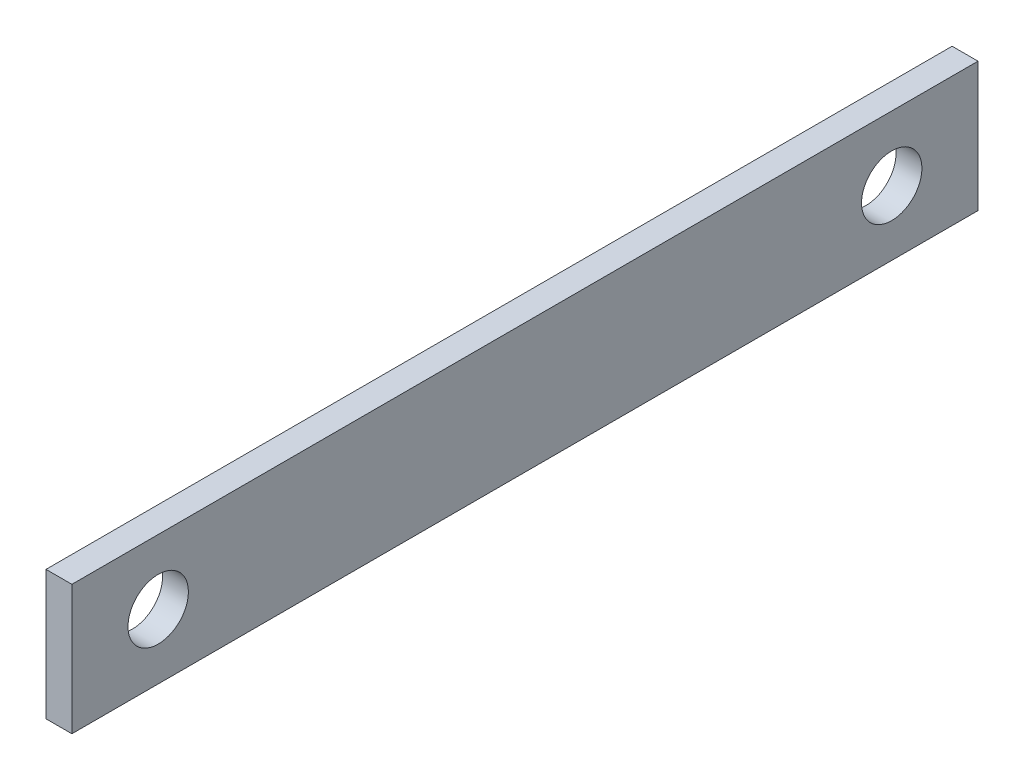
SolidWorks part; units mm, degrees
material "ASTM A36 Steel"
ref_plane "Front Plane" through (0, 0, 0) normal (0, 0, 1) x (1, 0, 0)
ref_plane "Top Plane" through (0, 0, 0) normal (0, 1, 0) x (1, 0, 0)
ref_plane "Right Plane" through (0, 0, 0) normal (1, 0, 0) x (0, 0, -1)
sketch "Sketch1" plane through (0, 0, 0) normal (1, 0, 0) x (0, 0, -1)
  line L1 (-105, -15) -> (105, -15)
  line L2 (-105, -15) -> (-105, 15)
  line L3 (-105, 15) -> (105, 15)
  line L4 (105, -15) -> (105, 15)
  line L5 (-105, -15) -> (105, 15) construction
  line L6 (-105, 15) -> (105, -15) construction
  circle A0 centre (-85, 0) radius 7
  circle A1 centre (85, 0) radius 7
  point P0 (0, 0)
  dimension "D3" = 14
  dimension "D4" = 14
  dimension "D5" = 20
  dimension "D6" = 20
  dimension "D1" = 30
  dimension "D2" = 210
extrude "Boss-Extrude1" add sketch "Sketch1" along normal blind 6
